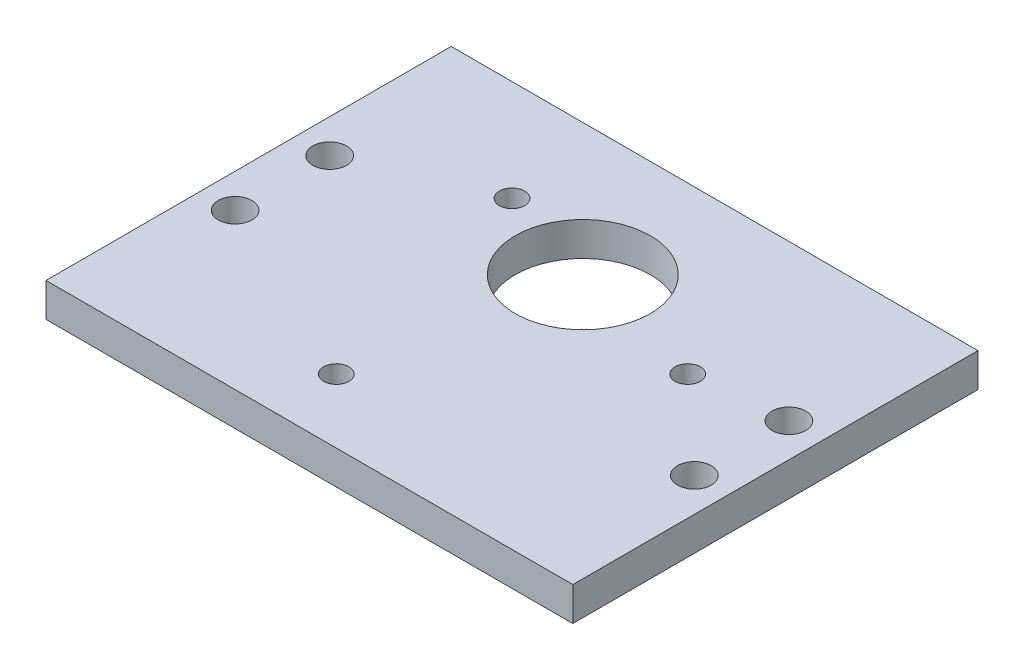
SolidWorks part; units mm, degrees
ref_plane "Front Plane" through (0, 0, 0) normal (0, 0, 1) x (1, 0, 0)
ref_plane "Top Plane" through (0, 0, 0) normal (0, 1, 0) x (1, 0, 0)
ref_plane "Right Plane" through (0, 0, 0) normal (1, 0, 0) x (0, 0, -1)
sketch "Sketch1" plane through (0, 0, 0) normal (0, 1, 0) x (1, 0, 0)
  line L1 (0, 0) -> (49.53, 0)
  line L2 (0, 0) -> (0, 38.1)
  line L3 (0, 38.1) -> (49.53, 38.1)
  line L4 (49.53, 0) -> (49.53, 38.1)
  dimension "D1" = 38.1
  dimension "D2" = 49.53
extrude "Boss-Extrude1" add sketch "Sketch1" along normal blind 3.175
sketch "Sketch4" plane through (0, 0, 0) normal (0, -1, 0) x (1, 0, 0)
  line L0 (24.765, 0) -> (24.765, -38.1) construction
  line L1 (0, 0) -> (49.53, 0) construction
  line L2 (49.53, -38.1) -> (0, -38.1) construction
  line L3 (21.2742, -6.0222) -> (24.765, -19.05) construction
  line L4 (0, -19.05) -> (49.53, -19.05) construction
  line L5 (0, -38.1) -> (0, 0) construction
  line L6 (49.53, 0) -> (49.53, -38.1) construction
  circle A0 centre (24.765, -19.05) radius 13.4874 construction
  circle A1 centre (21.2742, -6.0222) radius 1.1906
  circle A2 centre (37.7928, -22.5408) radius 1.1906
  circle A3 centre (15.228, -28.587) radius 1.1906
  circle A4 centre (24.765, -25.7048) radius 6.35
  circle A5 centre (3.175, -23.495) radius 1.5875
  circle A6 centre (3.175, -14.605) radius 1.5875
  circle A7 centre (46.355, -14.605) radius 1.5875
  circle A8 centre (46.355, -23.495) radius 1.5875
  point P17 (24.765, -19.05)
  dimension "D1" = 26.9748
  dimension "D2" = 2.3813
  dimension "D5" = 12.7
  dimension "D7" = 3.175
  dimension "D4" = 15
  dimension "D6" = 6.6548
  dimension "D8" = 3.175
  dimension "D9" = 4.445
  dimension "D3" = 3
extrude "Cut-Extrude2" cut sketch "Sketch4" against normal through all
